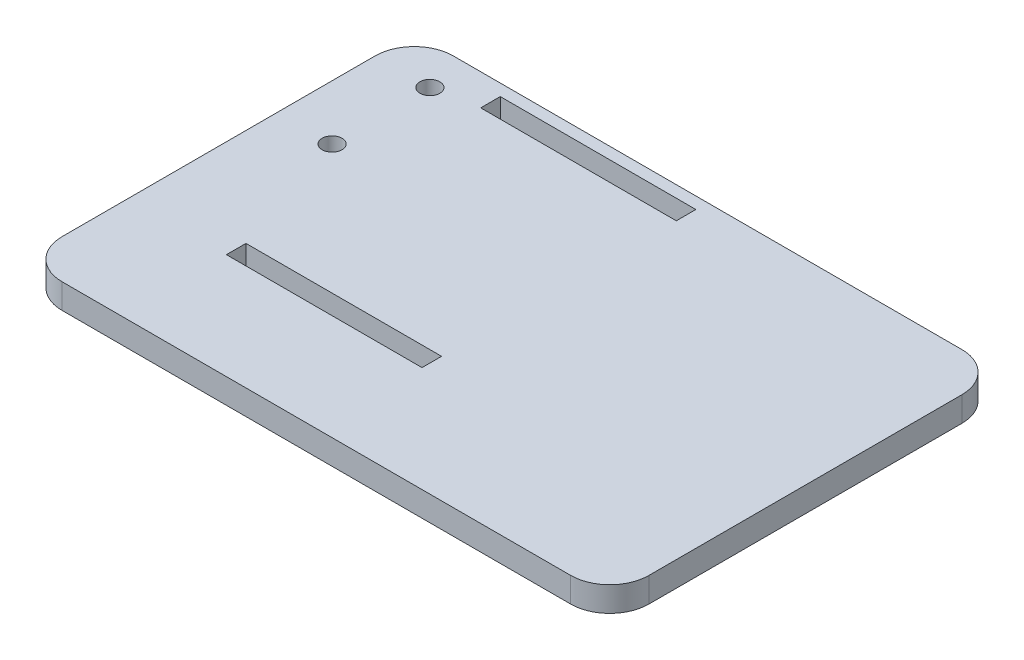
SolidWorks part; units mm, degrees
ref_plane "Front Plane" through (0, 0, 0) normal (0, 0, 1) x (1, 0, 0)
ref_plane "Top Plane" through (0, 0, 0) normal (0, 1, 0) x (1, 0, 0)
ref_plane "Right Plane" through (0, 0, 0) normal (1, 0, 0) x (0, 0, -1)
sketch "Sketch1" plane through (0, 0, 0) normal (0, 1, 0) x (1, 0, 0)
  line L0 (-75, 12) -> (75, 12) construction
  line L1 (-75, 50) -> (75, 50)
  line L2 (-75, 50) -> (-75, -50)
  line L3 (-75, -50) -> (75, -50)
  line L4 (75, 50) -> (75, -50)
  line L5 (-75, 50) -> (75, -50) construction
  line L6 (-75, -50) -> (75, 50) construction
  line L7 (-50, 47) -> (0, 47)
  line L8 (-50, 47) -> (-50, 42)
  line L9 (-50, 42) -> (0, 42)
  line L10 (0, 47) -> (0, 42)
  line L11 (-50, 47) -> (0, 42) construction
  line L12 (-50, 42) -> (0, 47) construction
  line L13 (-50, -18) -> (0, -23) construction
  line L14 (-50, -23) -> (0, -18) construction
  line L19 (0, -23) -> (0, -18)
  line L20 (-50, -18) -> (0, -18)
  line L21 (-50, -23) -> (-50, -18)
  line L22 (-50, -23) -> (0, -23)
  circle A0 centre (-61, 40) radius 2.55
  circle A1 centre (-61, 15) radius 2.55
  point P0 (0, 0)
  point P10 (-25, 44.5)
  point P21 (-25, -20.5)
  point P22 (0, 0)
  dimension "D2" = 5.1
  dimension "D1" = 25
  dimension "D3" = 10
  dimension "D4" = 14
  dimension "D5" = 150
  dimension "D6" = 100
  dimension "D7" = 50
  dimension "D8" = 5
  dimension "D9" = 3
  dimension "D10" = 25
  dimension "D11" = 30
extrude "Boss-Extrude1" add sketch "Sketch1" along normal blind 6.35
fillet "Fillet1" radius 10 4 edges at (-75, 3.175, -50) (75, 3.175, -50) (75, 3.175, 50) (-75, 3.175, 50)
